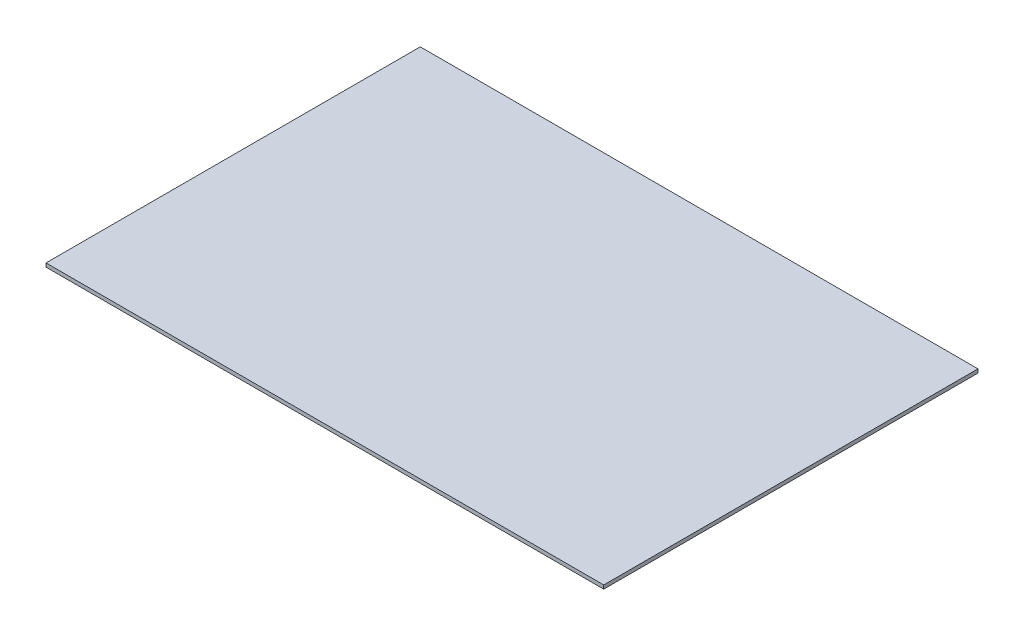
SolidWorks part; units mm, degrees
material "Acrylic (Medium-high impact)"
ref_plane "Front Plane" through (0, 0, 0) normal (0, 0, 1) x (1, 0, 0)
ref_plane "Top Plane" through (0, 0, 0) normal (0, 1, 0) x (1, 0, 0)
ref_plane "Right Plane" through (0, 0, 0) normal (1, 0, 0) x (0, 0, -1)
sketch "Sketch1" plane through (0, 0, 0) normal (0, 1, 0) x (1, 0, 0)
  line L1 (0, 0) -> (482.6, 0)
  line L2 (0, 0) -> (0, 323.85)
  line L3 (0, 323.85) -> (482.6, 323.85)
  line L4 (482.6, 0) -> (482.6, 323.85)
  dimension "D1" = 323.85
  dimension "D2" = 482.6
extrude "Boss-Extrude1" add sketch "Sketch1" along normal blind 3.175
